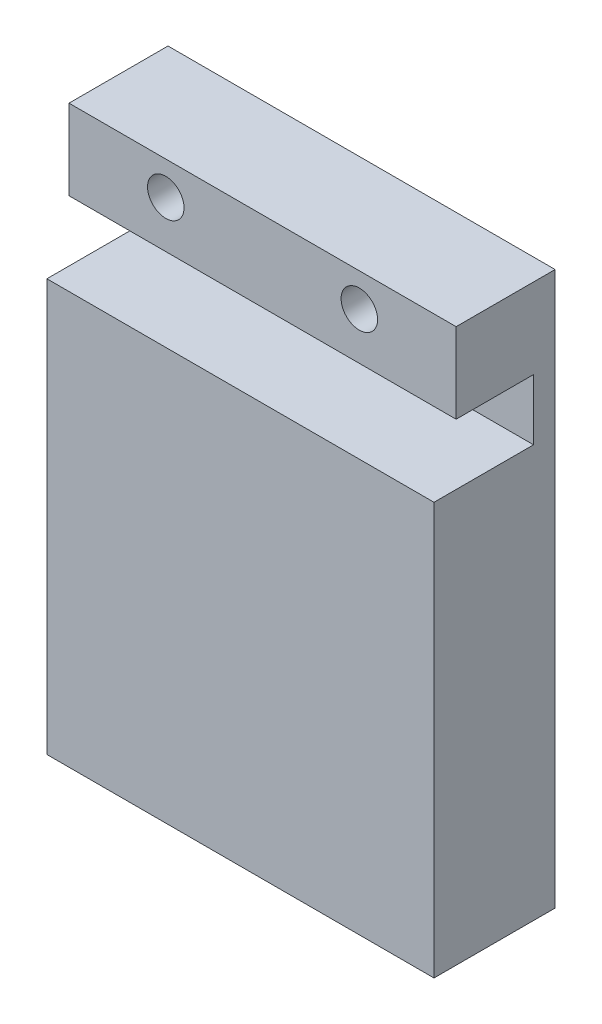
SolidWorks part; units mm, degrees
ref_plane "Ebene vorne" through (0, 0, 0) normal (0, 0, 1) x (1, 0, 0)
ref_plane "Ebene oben" through (0, 0, 0) normal (0, 1, 0) x (1, 0, 0)
ref_plane "Ebene rechts" through (0, 0, 0) normal (1, 0, 0) x (0, 0, -1)
sketch "Skizze1" plane through (0, 0, 0) normal (0, 0, 1) x (1, 0, 0)
  line L0 (-8.75, 22) -> (8.75, 22) construction
  line L1 (-17.5, -25) -> (17.5, -25)
  line L2 (-17.5, -25) -> (-17.5, 25)
  line L3 (-17.5, 25) -> (17.5, 25)
  line L4 (17.5, -25) -> (17.5, 25)
  line L5 (-17.5, -25) -> (17.5, 25) construction
  line L6 (-17.5, 25) -> (17.5, -25) construction
  circle A0 centre (-8.75, 22) radius 1.65
  circle A1 centre (8.75, 22) radius 1.65
  point P0 (0, 0)
  point P10 (0, 22)
  dimension "D4" = 3.3
  dimension "D5" = 3.3
  dimension "D1" = 50
  dimension "D2" = 35
  dimension "D3" = 3
  dimension "D6" = 17.5
extrude "Aufsatz-Linear austragen1" add sketch "Skizze1" along normal blind 10.95
sketch "Skizze2" plane through (0, 0, 10.95) normal (0, 0, 1) x (1, 0, 0)
  line L0 (17.5, 25) -> (-17.5, 25) construction
  line L1 (-25, 17.75) -> (25, 17.75)
  line L2 (-25, 17.75) -> (-25, 12.25)
  line L3 (-25, 12.25) -> (25, 12.25)
  line L4 (25, 17.75) -> (25, 12.25)
  line L5 (-25, 17.75) -> (25, 12.25) construction
  line L6 (-25, 12.25) -> (25, 17.75) construction
  point P4 (0, 15)
  point P5 (0, 0)
  dimension "D1" = 50
  dimension "D2" = 5.5
  dimension "D3" = 10
extrude "Schnitt-Linear austragen1" cut sketch "Skizze2" against normal blind 9
sketch "Skizze3" plane through (0, 0, 10.95) normal (0, 0, 1) x (1, 0, 0)
  line L1 (-17.5, 25) -> (17.5, 25)
  line L2 (-17.5, 25) -> (-17.5, 17.75)
  line L3 (-17.5, 17.75) -> (17.5, 17.75)
  line L4 (17.5, 25) -> (17.5, 17.75)
  line L5 (-17.5, 25) -> (17.5, 17.75) construction
  line L6 (-17.5, 17.75) -> (17.5, 25) construction
  point P4 (0, 21.375)
extrude "Schnitt-Linear austragen2" cut sketch "Skizze3" against normal blind 2
